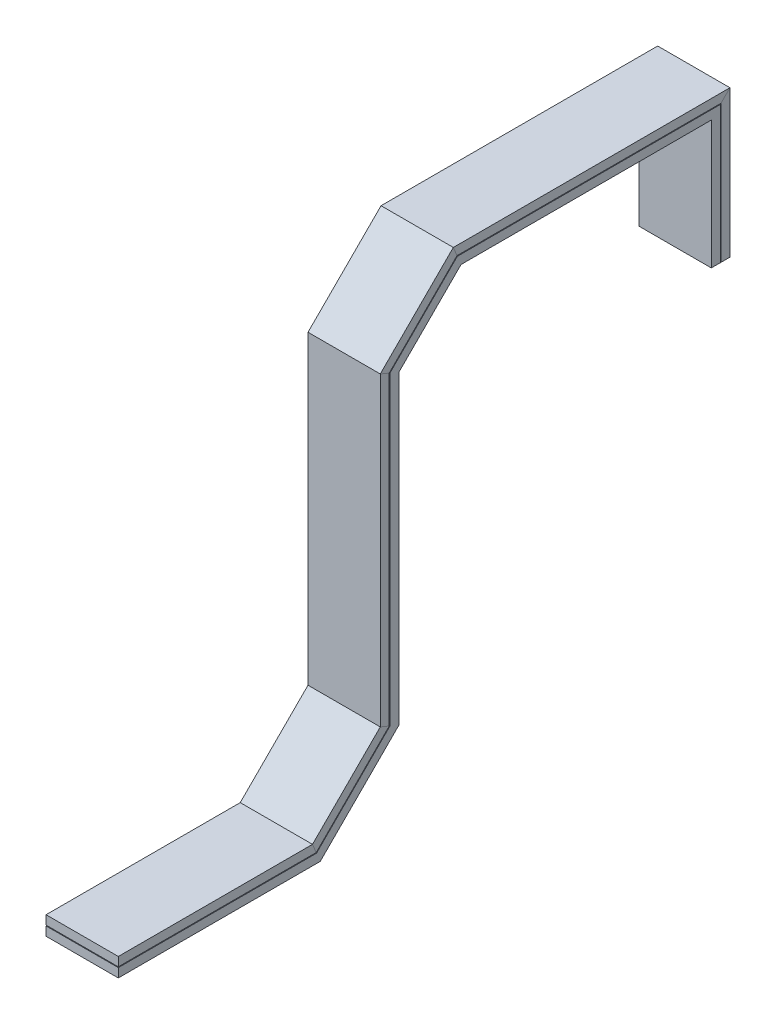
SolidWorks part; units mm, degrees
ref_plane "Alzado" through (0, 0, 0) normal (0, 0, 1) x (1, 0, 0)
ref_plane "Planta" through (0, 0, 0) normal (0, 1, 0) x (1, 0, 0)
ref_plane "Vista lateral" through (0, 0, 0) normal (1, 0, 0) x (0, 0, -1)
sketch "Croquis1" plane through (0, 0, 0) normal (0, 1, 0) x (1, 0, 0)
  line L1 (-25.4, 3.155) -> (25.4, 3.155)
  line L2 (-25.4, 3.155) -> (-25.4, -3.155)
  line L3 (-25.4, -3.155) -> (25.4, -3.155)
  line L4 (25.4, 3.155) -> (25.4, -3.155)
  line L5 (-25.4, 3.155) -> (25.4, -3.155) construction
  line L6 (-25.4, -3.155) -> (25.4, 3.155) construction
  point P0 (0, 0)
  dimension "D1" = 6.31
  dimension "D2" = 50.8
sketch3d "Croquis3D1"
  line L0 (0, 0, 0) -> (0, 100, 0)
  line L1 (0, 100, 0) -> (0, 100, 190)
  line L3 (0, 100, 190) -> (0, 50.5025, 239.4975)
  line L4 (0, 50.5025, 239.4975) -> (0, -164.3825, 239.4975)
  line L5 (0, -164.3825, 239.4975) -> (0, -213.88, 288.9949)
  line L7 (0, -213.88, 288.9949) -> (0, -213.88, 426.7949)
  dimension "D1" = 100
  dimension "D2" = 190
  dimension "D3" = 313.88
  dimension "D8" = 137.8
  dimension "D4" = 135
  dimension "D5" = 135
  dimension "D6" = 70
  dimension "D9" = 214.8851
  dimension "D7" = 70
sweep "Barrer1" add profiles "Croquis1" path "Croquis3D1"
sketch "Croquis2" plane through (-25.4, 0, 0) normal (-1, 0, 0) x (0, 0, 1)
  line L0 (3.155, 0) -> (3.155, 96.845) construction
  line L1 (3.155, 96.845) -> (188.6932, 96.845) construction
  line L2 (188.6932, 96.845) -> (236.3425, 49.1957) construction
  line L3 (236.3425, 49.1957) -> (236.3425, -165.6894) construction
  line L4 (236.3425, -165.6894) -> (287.6881, -217.035) construction
  line L5 (287.6881, -217.035) -> (426.7949, -217.035) construction
  line L6 (3.655, 0) -> (3.655, 96.345)
  line L7 (3.655, 96.345) -> (188.486, 96.345)
  line L8 (188.486, 96.345) -> (235.8425, 48.9886)
  line L9 (235.8425, 48.9886) -> (235.8425, -165.8965)
  line L10 (235.8425, -165.8965) -> (287.481, -217.535)
  line L11 (287.481, -217.535) -> (426.7949, -217.535)
  line L12 (9.965, 0) -> (9.965, 90.035)
  line L13 (9.965, 90.035) -> (185.8724, 90.035)
  line L14 (185.8724, 90.035) -> (229.5325, 46.3749)
  line L15 (229.5325, 46.3749) -> (229.5325, -168.5102)
  line L16 (229.5325, -168.5102) -> (284.8673, -223.845)
  line L17 (284.8673, -223.845) -> (426.7949, -223.845)
  line L18 (426.7949, -217.535) -> (426.7949, -223.845)
  line L19 (3.655, 0) -> (9.965, 0)
  dimension "D1" = 0.5
  dimension "D2" = 6.31
extrude "Saliente-Extruir1" add sketch "Croquis2" against normal blind 50.8 separate body
